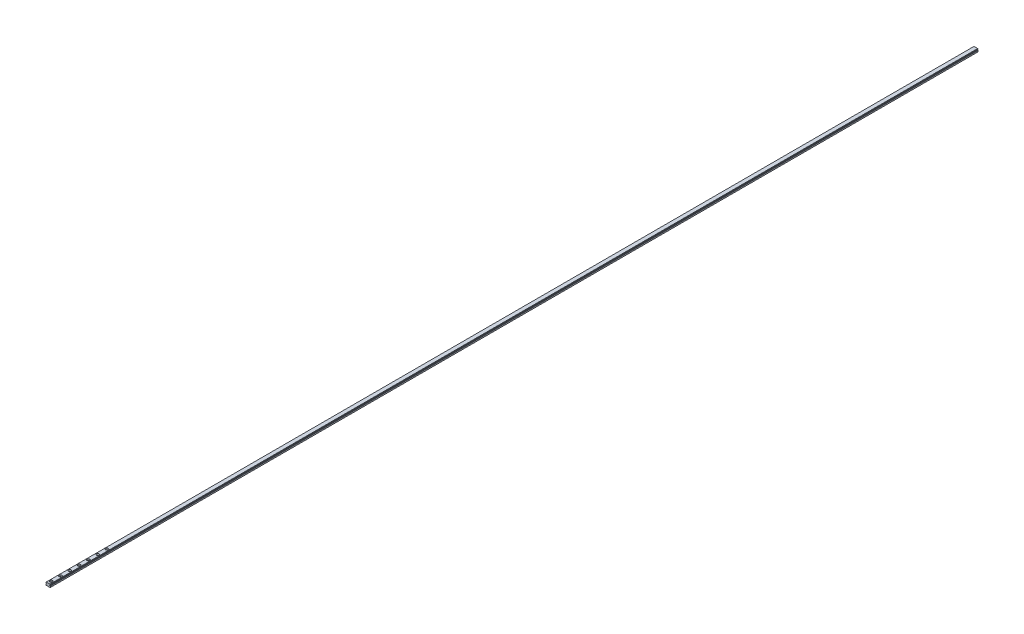
SolidWorks part; units mm, degrees
ref_plane "Front Plane" through (0, 0, 0) normal (0, 0, 1) x (1, 0, 0)
ref_plane "Top Plane" through (0, 0, 0) normal (0, 1, 0) x (1, 0, 0)
ref_plane "Right Plane" through (0, 0, 0) normal (1, 0, 0) x (0, 0, -1)
sketch "Sketch3" plane through (0, 0, 0) normal (0, 0, 1) x (1, 0, 0)
  line L0 (-3.5, 0) -> (-1.35, 0)
  line L1 (0, 0) -> (0, 4.8) construction
  line L2 (-3.5, 4.8) -> (3.5, 4.8)
  line L3 (-3.5, 0) -> (-3.5, 2.83)
  line L4 (3.5, 4.8) -> (3.5, 3.5)
  line L5 (-3.5, 3.5) -> (-2.65, 3.5)
  line L6 (-2.65, 3.5) -> (-2.65, 2.83) construction
  line L7 (-2.65, 2.83) -> (-3.5, 2.83)
  line L8 (-3.5, 3.5) -> (-3.5, 4.8)
  line L9 (2.65, 3.5) -> (2.65, 2.83) construction
  line L10 (2.65, 2.83) -> (3.5, 2.83)
  line L11 (3.5, 3.5) -> (2.65, 3.5)
  line L12 (3.5, 2.83) -> (3.5, 0)
  line L13 (-0.65, 0) -> (3.5, 0)
  arc A0 (-2.65, 3.5) -> (-2.65, 2.83) centre (-2.65, 3.165) cw
  arc A1 (2.65, 3.5) -> (2.65, 2.83) centre (2.65, 3.165) ccw
  arc A2 (-1.35, 0) -> (-0.65, 0) centre (-1, -0.3571) cw
  point P8 (0, 4.8)
  dimension "D8" = 0.5
  dimension "D1" = 7
  dimension "D2" = 4.8
  dimension "D3" = 1.3
  dimension "D4" = 2.65
  dimension "D5" = 0.67
  dimension "D6" = 1
  dimension "D7" = 0.7
extrude "Boss-Extrude1" add sketch "Sketch3" along normal mid plane 1500
chamfer "Chamfer1" distance 0.5 angle 45 2 edges at (3.5, 4.8, 0) (-3.5, 4.8, 0)
chamfer "Chamfer2" distance 0.3 angle 45 6 edges at (3.5, 0, 0) (-3.5, 0, 0) (-3.5, 2.83, 0) (3.5, 2.83, 0) (3.5, 3.5, 0) (-3.5, 3.5, 0)
hole_wizard "CBORE for M2 SHCS1" positions "Sketch4" profile "Sketch5" counterbore size "M2" standard "ANSI Metric" end condition up to next
sketch "Sketch4" plane through (0, 4.8, 0) normal (0, 1, 0) x (1, 0, 0)
  line L0 (3, -750) -> (-3, -750) construction
  point P0 (0, -745)
  dimension "D1" = 5
sketch "Sketch5" plane through (0, 4.8, 745) normal (1, 0, 0) x (0, 0, 1)
  line L0 (0, 0) -> (0, 4.8)
  line L1 (0, 4.8) -> (1.2, 4.8)
  line L3 (1.2, 4.8) -> (1.2, 2.65)
  line L4 (1.2, 2.65) -> (2.2, 2.65)
  line L5 (2.2, 2.65) -> (2.2, 0)
  line L7 (2.2, 0) -> (0, 0)
  line L11 (0, -6.35) -> (0, 107.95) construction
  dimension "Thru Hole Dia." = 2.4
  dimension "Thru Hole Depth" = 4.8
  dimension "C'Bore Dia." = 4.4
  dimension "C'Bore Depth" = 2.65
pattern_linear "LPattern1" count 7 spacing 15 along (0, 0, -1) of "CBORE for M2 SHCS1"
